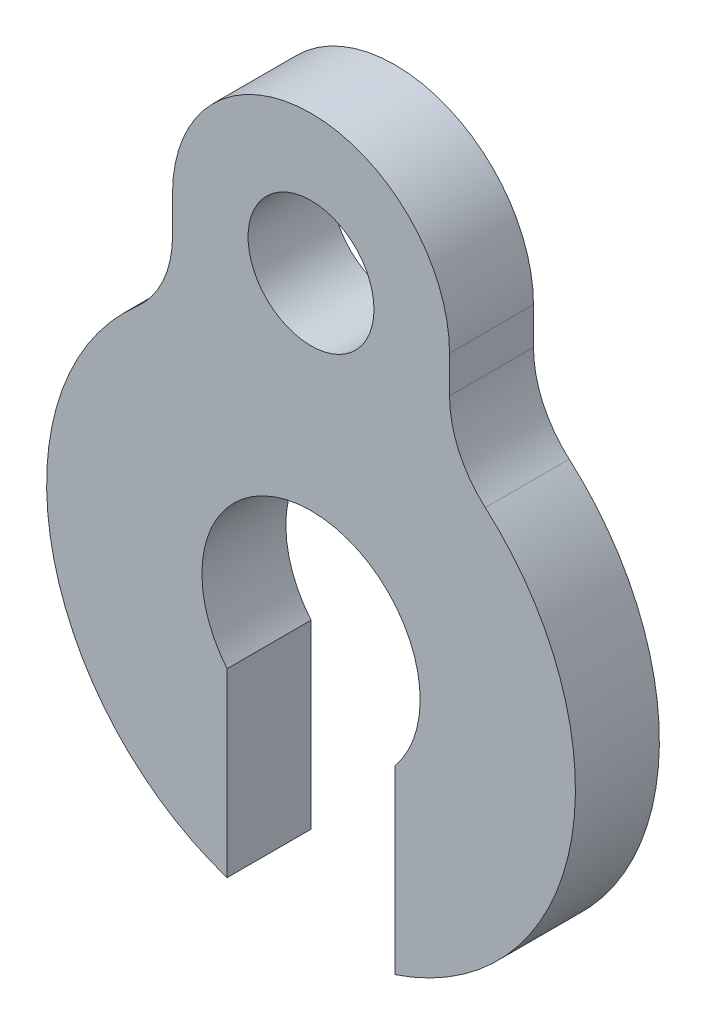
SolidWorks part; units mm, degrees
material "Plain Carbon Steel"
ref_plane "Front Plane" through (0, 0, 0) normal (0, 0, 1) x (1, 0, 0)
ref_plane "Top Plane" through (0, 0, 0) normal (0, 1, 0) x (1, 0, 0)
ref_plane "Right Plane" through (0, 0, 0) normal (1, 0, 0) x (0, 0, -1)
sketch "Sketch1" plane through (0, 0, 0) normal (0, 0, 1) x (1, 0, 0)
  line L0 (0, -24.2198) -> (0, 1186.7702) construction
  line L1 (-2.0955, 3.4078) -> (-2.0955, 4.7625)
  line L2 (2.0955, 4.7625) -> (2.0955, 3.4078)
  line L3 (-1.27, -3.7936) -> (-1.27, -1.0549)
  line L4 (1.27, -3.7936) -> (1.27, -1.0549)
  circle A0 centre (0, 0) radius 1.651 construction
  circle A1 centre (0, 4.7625) radius 0.9525
  arc A2 (-2.0955, 4.7625) -> (2.0955, 4.7625) centre (0, 4.7625) cw
  arc A3 (-2.0955, 3.4078) -> (-1.27, -3.7936) centre (0, 0) ccw
  arc A4 (2.0955, 3.4078) -> (1.27, -3.7936) centre (0, 0) cw
  arc A5 (-1.27, -1.0549) -> (1.27, -1.0549) centre (0, 0) cw
  dimension "D1" = 3.302
  dimension "D2" = 1.905
  dimension "D4" = 2.0955
  dimension "D5" = 4.0005
  dimension "D3" = 4.7625
  dimension "D6" = 2.54
extrude "Boss-Extrude1" add sketch "Sketch1" along normal blind 1.27 contours L3 A5 L4 A4 L2 A2 L1 A3 A1
fillet "Fillet1" radius 1.5875 2 edges at (-2.0955, 3.4078, 0.635) (2.0955, 3.4078, 0.635)
